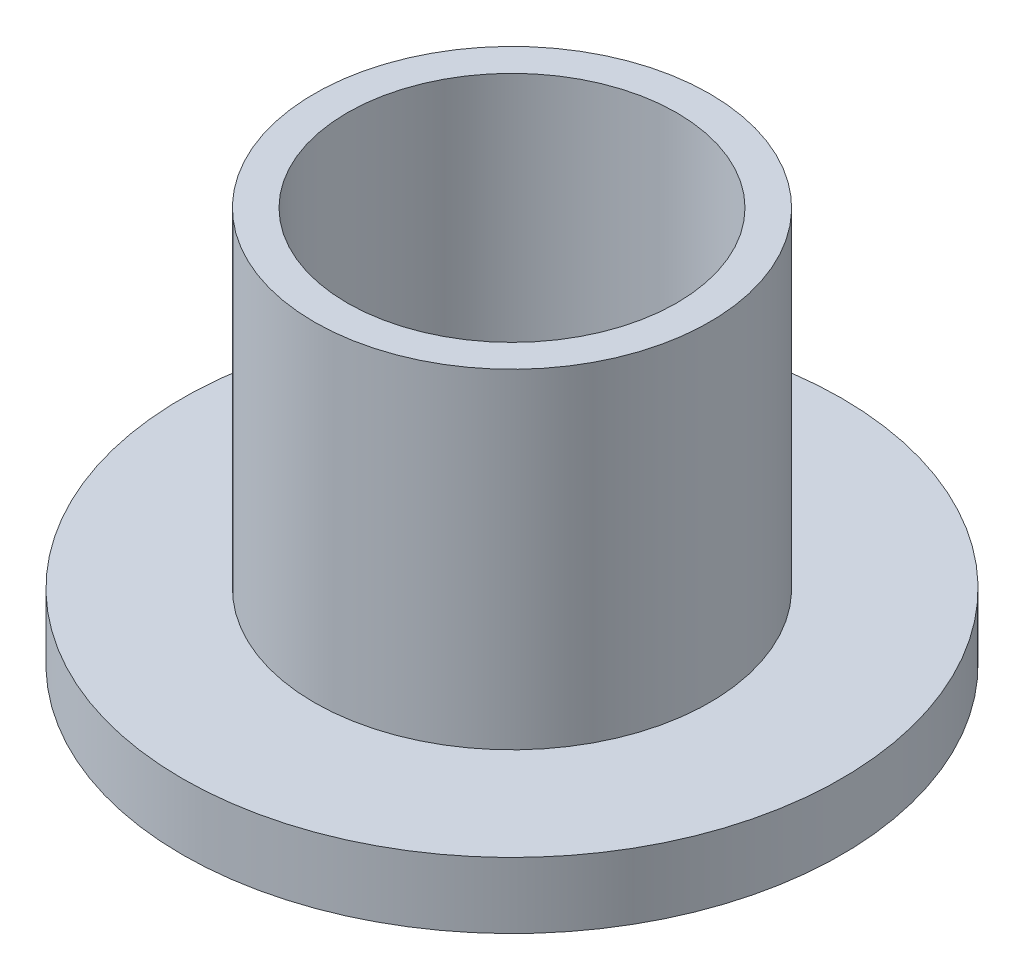
SolidWorks part; units mm, degrees
ref_plane "前视基准面" through (0, 0, 0) normal (0, 0, 1) x (1, 0, 0)
ref_plane "上视基准面" through (0, 0, 0) normal (0, 1, 0) x (1, 0, 0)
ref_plane "右视基准面" through (0, 0, 0) normal (1, 0, 0) x (0, 0, -1)
sketch "草图1" plane through (0, 0, 0) normal (0, 0, 1) x (1, 0, 0)
  line L0 (0, 0) -> (0, 16.0558) construction
  line L1 (2.5, 0) -> (2.5, 6)
  line L2 (2.5, 6) -> (3, 6)
  line L3 (3, 6) -> (3, 1)
  line L4 (3, 1) -> (5, 1)
  line L5 (5, 1) -> (5, 0)
  line L6 (5, 0) -> (2.5, 0)
  dimension "D1" = 5
  dimension "D2" = 1
  dimension "D3" = 2.5
  dimension "D4" = 3
  dimension "D5" = 5
revolve "旋转1" add sketch "草图1" angle 360 about L0
